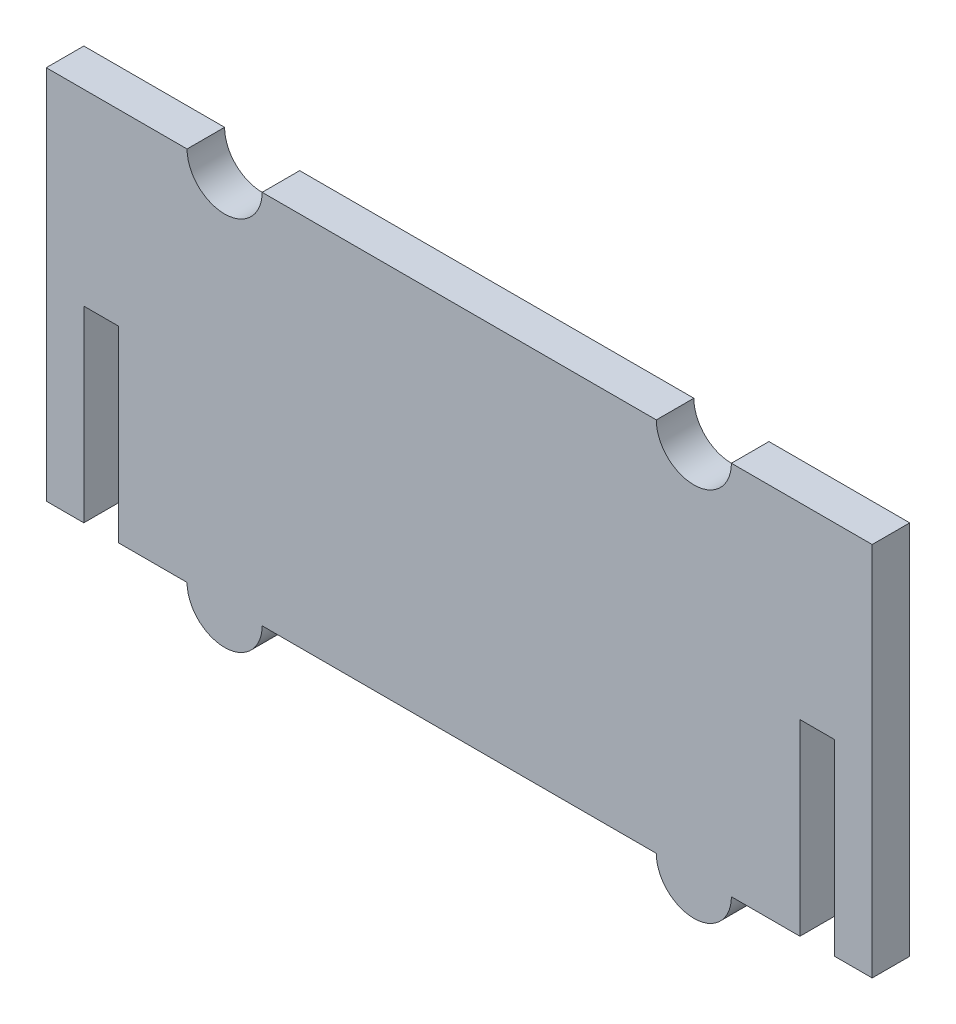
SolidWorks part; units mm, degrees
ref_plane "Front Plane" through (0, 0, 0) normal (0, 0, 1) x (1, 0, 0)
ref_plane "Top Plane" through (0, 0, 0) normal (0, 1, 0) x (1, 0, 0)
ref_plane "Right Plane" through (0, 0, 0) normal (1, 0, 0) x (0, 0, -1)
sketch "Sketch1" plane through (0, 0, 0) normal (0, 0, 1) x (1, 0, 0)
  line L0 (7.7, 0) -> (15, 0)
  line L1 (0, 0) -> (4, 0)
  line L2 (0, 0) -> (0, 40)
  line L3 (0, 40) -> (15, 40)
  line L4 (88, 0) -> (88, 40)
  line L5 (44, 40) -> (44, -5.1611) construction
  line L6 (4, 0) -> (4, 20)
  line L7 (4, 20) -> (7.7, 20)
  line L8 (7.7, 0) -> (7.7, 20)
  line L9 (80.3, 0) -> (80.3, 20)
  line L10 (84, 20) -> (80.3, 20)
  line L11 (84, 0) -> (84, 20)
  line L12 (84, 0) -> (88, 0)
  line L13 (73, 0) -> (80.3, 0)
  line L14 (73, 40) -> (88, 40)
  line L15 (23, 40) -> (65, 40)
  line L16 (23, 0) -> (65, 0)
  arc A0 (65, 40) -> (73, 40) centre (69, 40) ccw
  arc A1 (65, 0) -> (73, 0) centre (69, 0) ccw
  arc A2 (23, 0) -> (15, 0) centre (19, 0) cw
  arc A3 (23, 40) -> (15, 40) centre (19, 40) cw
  dimension "D6" = 8
  dimension "D1" = 88
  dimension "D2" = 40
  dimension "D3" = 20
  dimension "D4" = 3.7
  dimension "D5" = 4
  dimension "D7" = 50
extrude "Boss-Extrude1" add sketch "Sketch1" along normal blind 4
